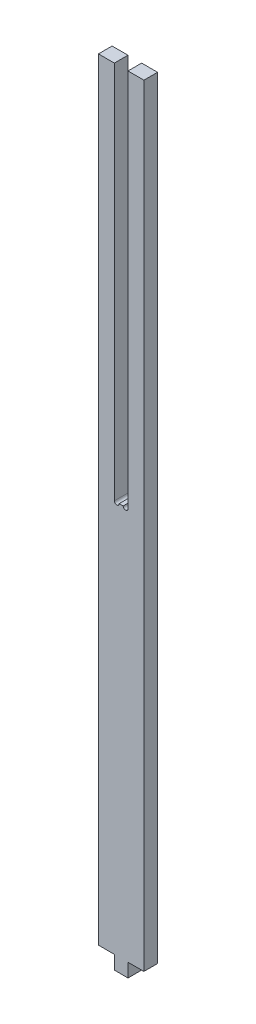
SolidWorks part; units mm, degrees
ref_plane "Piano frontale" through (0, 0, 0) normal (0, 0, 1) x (1, 0, 0)
ref_plane "Piano superiore" through (0, 0, 0) normal (0, 1, 0) x (1, 0, 0)
ref_plane "Piano destro" through (0, 0, 0) normal (1, 0, 0) x (0, 0, -1)
sketch "Schizzo1" plane through (0, 0, 0) normal (0, 0, 1) x (1, 0, 0)
  line L0 (-51.2222, 843) -> (-51.2222, 343)
  line L1 (-72.2222, 843) -> (-51.2222, 843)
  line L2 (-72.2222, 843) -> (-72.2222, -175)
  line L3 (-72.2222, -175) -> (-51.2222, -175)
  line L4 (-12.2222, 843) -> (-12.2222, -175)
  line L5 (-42.2222, 343) -> (-42.2222, -799.501) construction
  line L6 (-33.2222, -175) -> (-12.2222, -175)
  line L7 (-44.8722, 343) -> (-39.5722, 343)
  line L8 (-33.2222, 343) -> (-33.2222, 843)
  line L9 (-33.2222, 843) -> (-12.2222, 843)
  line L11 (-51.2222, -175) -> (-51.2222, -193)
  line L12 (-51.2222, -193) -> (-33.2222, -193)
  line L13 (-33.2222, -175) -> (-33.2222, -193)
  arc A0 (-33.2222, 343) -> (-39.5722, 343) centre (-36.3972, 343) cw
  arc A1 (-51.2222, 343) -> (-44.8722, 343) centre (-48.0472, 343) ccw
  point P0 (-42.766, 343)
  dimension "D5" = 3.175
  dimension "D6" = 3.175
  dimension "D1" = 60
  dimension "D2" = 1018
  dimension "D3" = 18
  dimension "D4" = 21
  dimension "D7" = 18
  dimension "D8" = 18
extrude "Estrusione-Estrusione1" add sketch "Schizzo1" along normal blind 18 contours L4 L6 L13 L12 L11 L3 L2 L1 L0 A1 L7 A0 L8 L9
